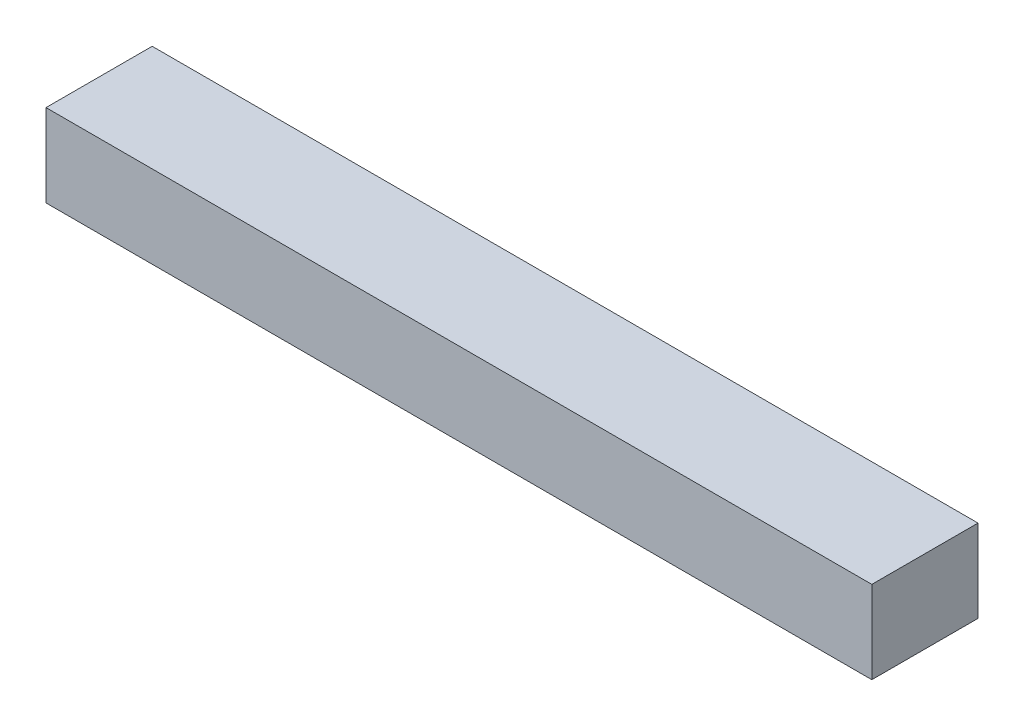
SolidWorks part; units mm, degrees
ref_plane "Front Plane" through (0, 0, 0) normal (0, 0, 1) x (1, 0, 0)
ref_plane "Top Plane" through (0, 0, 0) normal (0, 1, 0) x (1, 0, 0)
ref_plane "Right Plane" through (0, 0, 0) normal (1, 0, 0) x (0, 0, -1)
sketch "Sketch1" plane through (0, 0, 0) normal (0, 1, 0) x (1, 0, 0)
  line L1 (0, 0) -> (70, 0)
  line L2 (0, 0) -> (0, 9)
  line L3 (0, 9) -> (70, 9)
  line L4 (70, 0) -> (70, 9)
  dimension "D1" = 70
  dimension "D2" = 9
extrude "Boss-Extrude1" add sketch "Sketch1" along normal blind 7
